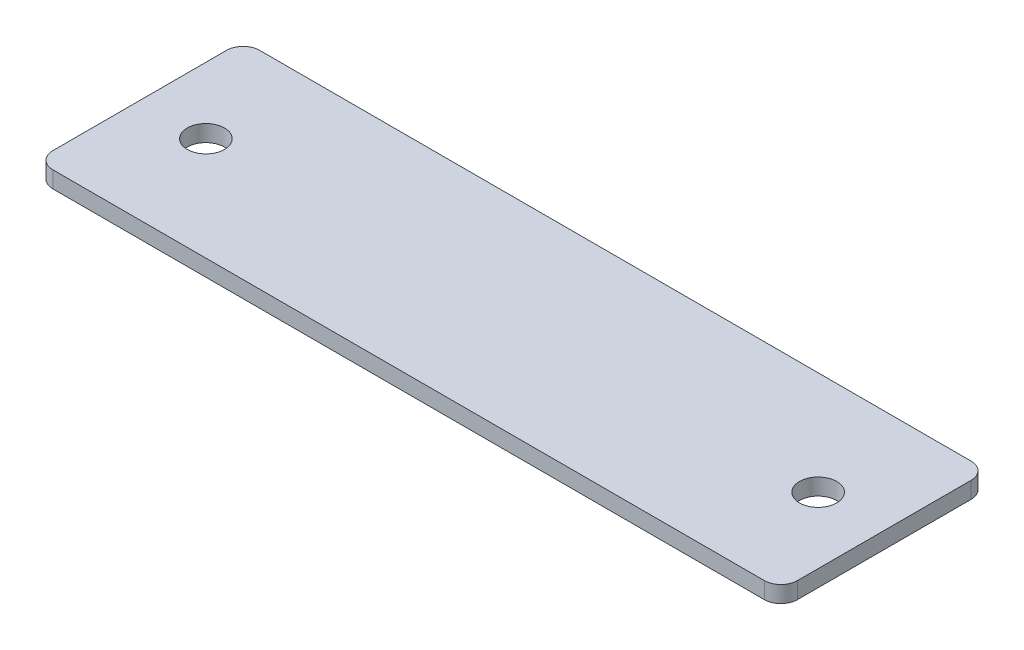
SolidWorks part; units mm, degrees
ref_plane "Plan de face" through (0, 0, 0) normal (0, 0, 1) x (1, 0, 0)
ref_plane "Plan de dessus" through (0, 0, 0) normal (0, 1, 0) x (1, 0, 0)
ref_plane "Plan de droite" through (0, 0, 0) normal (1, 0, 0) x (0, 0, -1)
sketch "Esquisse1" plane through (0, 0, 0) normal (0, 0, 1) x (1, 0, 0)
  line L0 (0, 0) -> (90, 0)
  dimension "D1" = 90
extrude "Extru.-Mince1" add sketch "Esquisse1" along normal blind 25 thin
fillet "Congé1" radius 2 1 edges at (90, -1, 25)
fillet "Congé2" radius 2 1 edges at (90, -1, 0)
fillet "Congé3" radius 2 1 edges at (0, -1, 0)
fillet "Congé4" radius 2 1 edges at (0, -1, 25)
sketch "Esquisse2" plane through (0, 0, 0) normal (0, 1, 0) x (1, 0, 0)
  line L0 (90, -23) -> (90, -2) construction
  line L1 (0, -23) -> (0, -2) construction
  line L2 (2, 0) -> (88, 0) construction
  circle A0 centre (82, -12.5) radius 2.25
  circle A1 centre (8, -12.5) radius 2.25
  dimension "D1" = 4.5
  dimension "D2" = 4.5
  dimension "D3" = 8
  dimension "D4" = 8
  dimension "D5" = 12.5
  dimension "D6" = 12.5
extrude "Enlèv. mat.-Extru.1" cut sketch "Esquisse2" against normal blind 10
